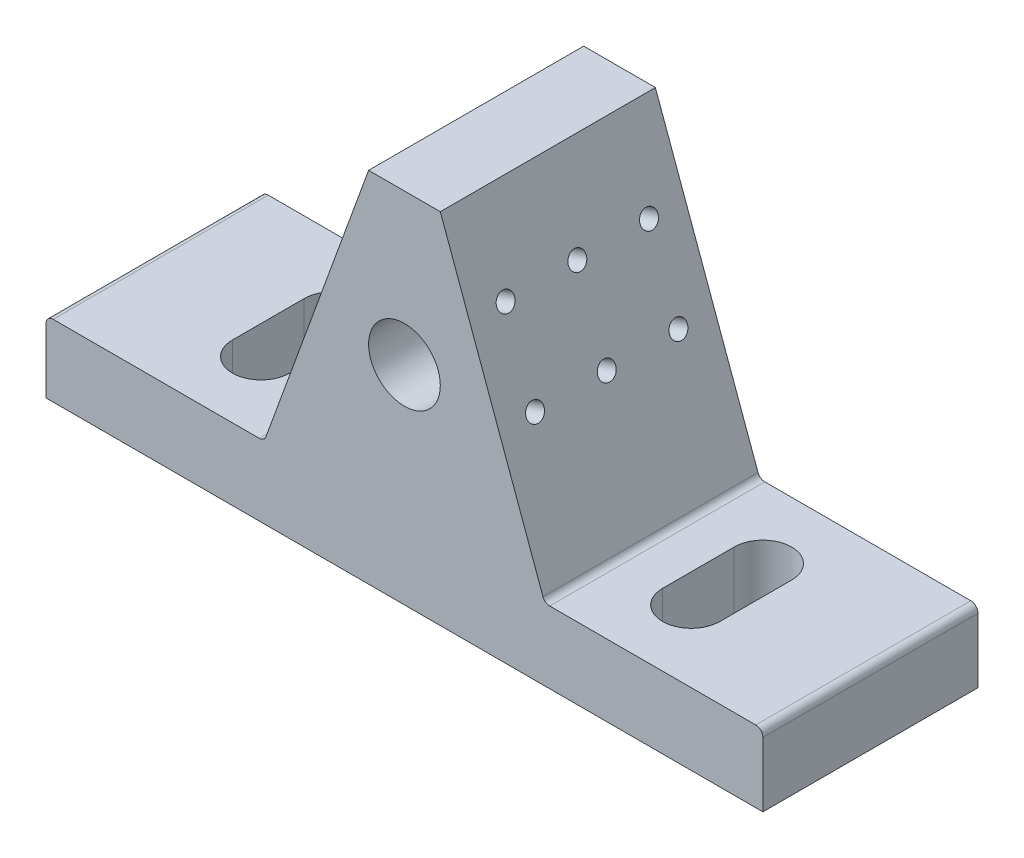
SolidWorks part; units mm, degrees
material "AISI 304"
ref_plane "Front Plane" through (0, 0, 0) normal (0, 0, 1) x (1, 0, 0)
ref_plane "Top Plane" through (0, 0, 0) normal (0, 1, 0) x (1, 0, 0)
ref_plane "Right Plane" through (0, 0, 0) normal (1, 0, 0) x (0, 0, -1)
sketch "Sketch1" plane through (0, 0, 0) normal (0, 0, 1) x (1, 0, 0)
  line L0 (0, 0) -> (0, 50) construction
  line L1 (-50, 0) -> (50, 0)
  line L2 (50, 0) -> (50, 10)
  line L3 (-50, 0) -> (-50, 10)
  line L4 (50, 10) -> (19.5588, 10)
  line L5 (-50, 10) -> (-19.5588, 10)
  line L6 (19.5588, 10) -> (5, 50)
  line L7 (-19.5588, 10) -> (-5, 50)
  line L8 (5, 50) -> (-5, 50)
  dimension "D1" = 110
  dimension "D2" = 10
  dimension "D3" = 50
  dimension "D4" = 10
  dimension "D5" = 100
extrude "Base Extrude" add sketch "Sketch1" along normal mid plane 30
sketch "Sketch2" plane through (0, 10, 0) normal (0, 1, 0) x (1, 0, 0)
  line L0 (30, -5) -> (30, 5) construction
  line L1 (26, -5) -> (26, 5)
  line L2 (34, -5) -> (34, 5)
  line L3 (50, 15) -> (19.5588, 15) construction
  arc A0 (26, -5) -> (34, -5) centre (30, -5) ccw
  arc A1 (34, 5) -> (26, 5) centre (30, 5) ccw
  point P2 (30, 0)
  dimension "D4" = 4
  dimension "D1" = 30
  dimension "D2" = 10
  dimension "D3" = 10
extrude "Slot Cut" cut sketch "Sketch2" against normal through all
mirror "Mirror1" about plane through (0, 0, 0) normal (1, 0, 0) of "Slot Cut"
sketch "Sketch3" plane through (0, 0, 15) normal (0, 0, 1) x (1, 0, 0)
  circle A0 centre (0, 29) radius 5
  dimension "D1" = 10
  dimension "D2" = 29
extrude "Guide hole" cut sketch "Sketch3" against normal through all
hole_wizard "M3x0.5 Tapped Hole3" positions "Sketch11" profile "Sketch10" tap size "M3x0.5" standard "ANSI Metric"
sketch "Sketch11" plane through (20.4848, 7.4559, 0) normal (0.9397, 0.342, 0) x (0, 0, -1)
  line L0 (15, 2.7074) -> (15, 45.2745) construction
  line L1 (15, 27.2511) -> (-15, 27.2511) construction
  point P0 (-10, 21.2511)
  dimension "D1" = 25
  dimension "D2" = 6
sketch "Sketch10" plane through (13.2165, 27.4253, 10) normal (0, 0, 1) x (-0.342, 0.9397, 0)
  line L0 (0, 0) -> (0, 8.2511)
  line L1 (0, 8.2511) -> (1.25, 7.5)
  line L2 (1.25, 7.5) -> (1.25, 0)
  line L5 (1.25, 0) -> (0, 0)
  line L10 (0, 8.2511) -> (-1.25, 7.5) construction
  line L11 (0, -6.35) -> (0, 107.95) construction
  dimension "Tap Drill Dia." = 2.5
  dimension "Tap Drill Depth" = 7.5
  dimension "Drill Angle" = 118
cosmetic thread "Hole Thread1" parameters "D1"=6, "D2"=3
pattern_linear "LPattern1" count 3 spacing 10 along (0, 0, -1) count 2 spacing 12 along (-0.342, 0.9397, 0) of "M3x0.5 Tapped Hole3"
fillet "Fillet1" radius 1 4 edges at (-19.5588, 10, 0) (-50, 10, 0) (50, 10, 0) (19.5588, 10, 0)
